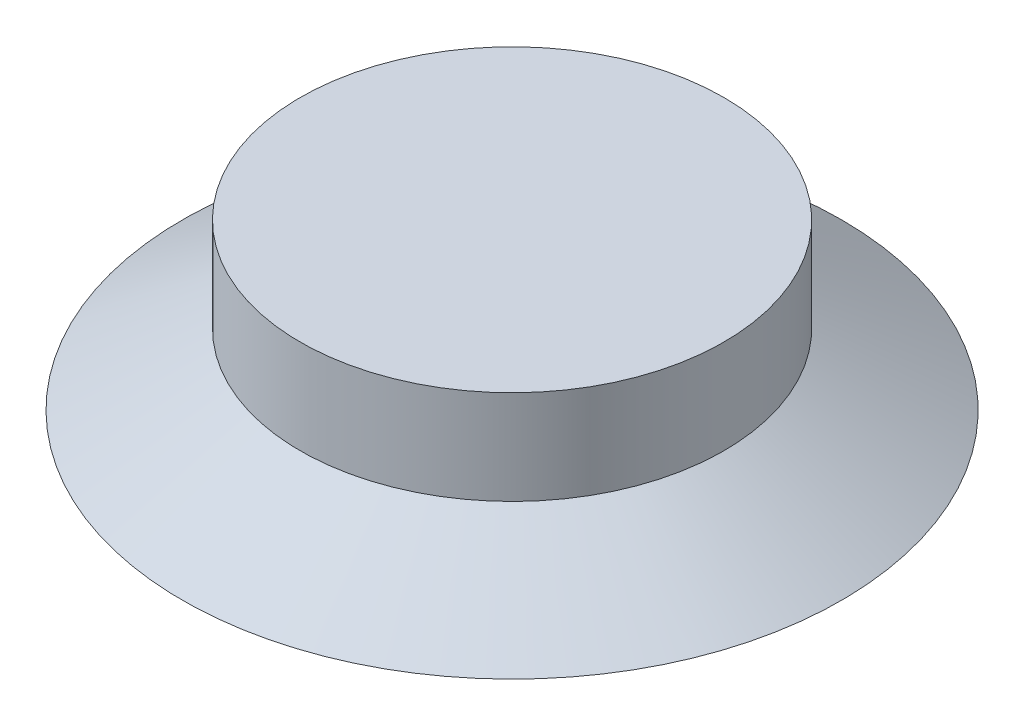
SolidWorks part; units mm, degrees
material "Acero al carbono no aleado"
ref_plane "Alzado" through (0, 0, 0) normal (0, 0, 1) x (1, 0, 0)
ref_plane "Planta" through (0, 0, 0) normal (0, 1, 0) x (1, 0, 0)
ref_plane "Vista lateral" through (0, 0, 0) normal (1, 0, 0) x (0, 0, -1)
sketch "Croquis1" plane through (0, 0, 0) normal (0, 0, 1) x (1, 0, 0)
  line L0 (2.25, -1) -> (4.75, -2.5)
  line L1 (2.25, -1) -> (-2.25, -1)
  line L2 (2.25, -1) -> (2.25, 1)
  line L3 (2.25, 1) -> (-2.25, 1)
  line L4 (-2.25, -1) -> (-2.25, 1)
  line L5 (2.25, -1) -> (-2.25, 1) construction
  line L6 (2.25, 1) -> (-2.25, -1) construction
  line L7 (4.75, -2.5) -> (-2.25, -2.5)
  line L8 (-2.25, -2.5) -> (-2.25, -1)
  point P0 (0, 0)
  dimension "D1" = 4.5
  dimension "D2" = 2
  dimension "D3" = 7
  dimension "D4" = 1.5
revolve "Revolución1" add sketch "Croquis1" angle 360 about L4
